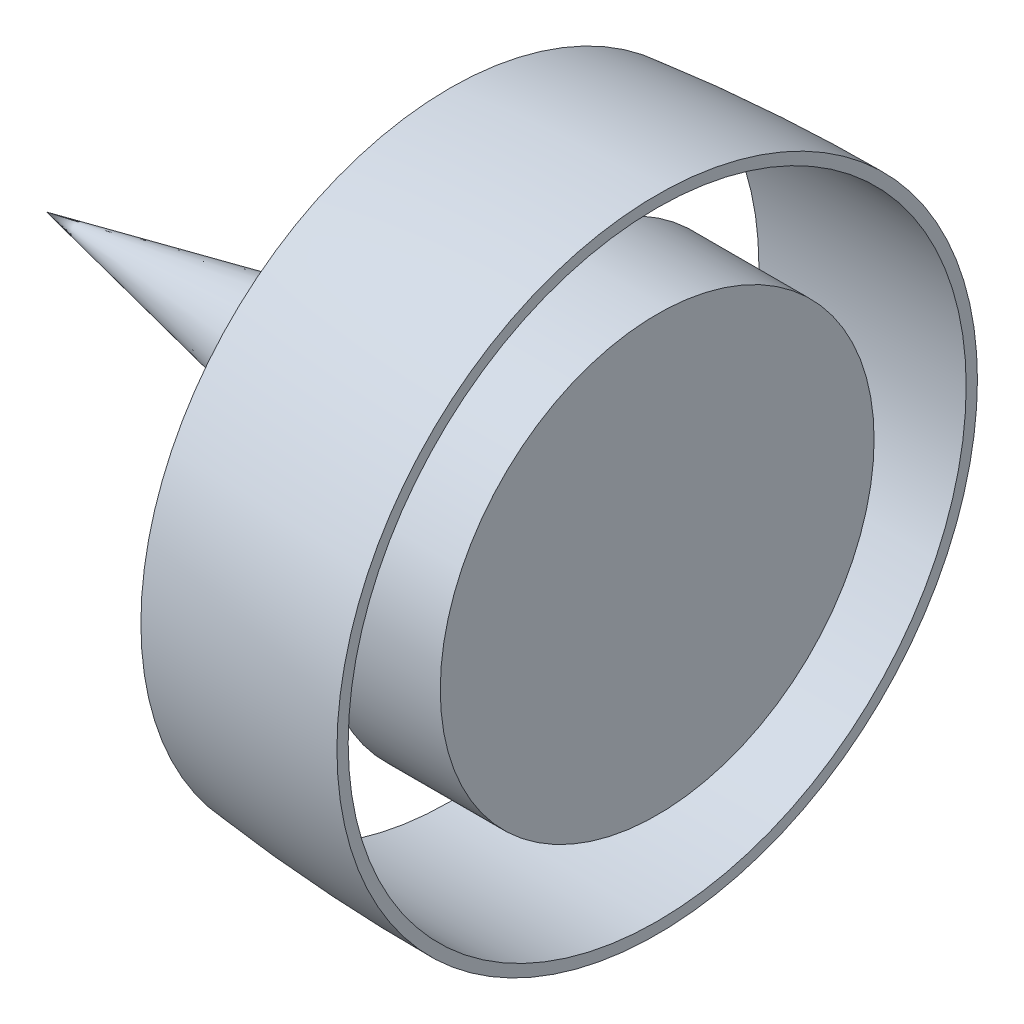
SolidWorks part; units mm, degrees
ref_plane "Piano frontale" through (0, 0, 0) normal (0, 0, 1) x (1, 0, 0)
ref_plane "Piano superiore" through (0, 0, 0) normal (0, 1, 0) x (1, 0, 0)
ref_plane "Piano destro" through (0, 0, 0) normal (1, 0, 0) x (0, 0, -1)
sketch "Schizzo1" plane through (0, 0, 0) normal (0, 0, 1) x (1, 0, 0)
  line L0 (0, 0) -> (436.8379, 91.2602)
  line L1 (436.8379, 91.2602) -> (706.9223, 224.1582)
  line L2 (706.9223, 224.1582) -> (869.6609, 380.7651)
  line L3 (0, 0) -> (436.8379, 91.2602)
  line L4 (0, 0) -> (869.6609, 0)
  line L5 (869.6609, 0) -> (869.6609, 380.7651) construction
  line L6 (0, 0) -> (707.2641, 549.5204) construction
  line L7 (707.2641, 549.5204) -> (436.8379, 91.2602) construction
  line L8 (869.6609, 380.7651) -> (707.2641, 549.5204) construction
  line L9 (707.2641, 549.5204) -> (706.9223, 224.1582) construction
  line L10 (869.6609, 380.7651) -> (874.8529, 385.7614)
  line L11 (707.2641, 549.5204) -> (717.2641, 549.5204) construction
  line L12 (717.2641, 549.5204) -> (874.8529, 385.7614) construction
  line L13 (874.8529, 385.7614) -> (1085.8726, 385.7614)
  line L14 (1085.8726, 385.7614) -> (1085.8726, 0)
  line L15 (1085.8726, 0) -> (869.6609, 0)
  line L16 (717.2641, 549.5204) -> (1085.8726, 549.5204)
  line L17 (512.9432, 569.5204) -> (50512.9432, 569.5204) construction
  line L19 (1085.8726, 569.5204) -> (1085.8726, 549.5204)
  line L20 (-275.0185, 0) -> (49724.9815, 0) construction
  arc A0 (717.2641, 549.5204) -> (1085.8726, 569.5204) centre (1085.8726, -2837.2837) cw
  dimension "D1" = 11.8
  dimension "D2" = 26.2
  dimension "D3" = 43.9
  dimension "D4" = 26.046
  dimension "D5" = 33.255
  dimension "D6" = 46.04
  dimension "D7" = 227.269
  dimension "D8" = 10
  dimension "D9" = 20
  dimension "D10" = 216.2116
revolve "Rivoluzione1" add sketch "Schizzo1" angle 360 about L20
